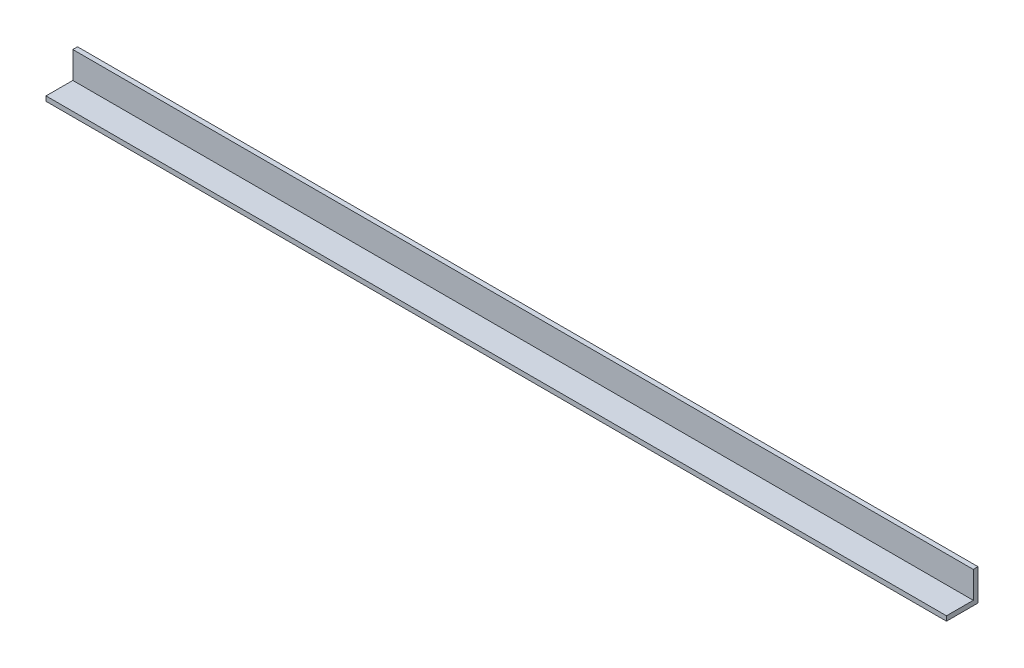
SolidWorks part; units mm, degrees
ref_plane "前视基准面" through (0, 0, 0) normal (0, 0, 1) x (1, 0, 0)
ref_plane "上视基准面" through (0, 0, 0) normal (0, 1, 0) x (1, 0, 0)
ref_plane "右视基准面" through (0, 0, 0) normal (1, 0, 0) x (0, 0, -1)
sketch "草图1" plane through (0, 0, 0) normal (0, 0, 1) x (1, 0, 0)
  line L1 (0, 0) -> (2286, 0)
  line L2 (0, 0) -> (0, 80)
  line L3 (0, 80) -> (2286, 80)
  line L4 (2286, 0) -> (2286, 80)
  dimension "D1" = 2286
  dimension "D2" = 80
extrude "拉伸1" add sketch "草图1" along normal blind 80
sketch "草图3" plane through (0, 0, 0) normal (-1, 0, 0) x (0, 0, 1)
  line L0 (80, 80) -> (80, 0) construction
  line L1 (12, 80) -> (80, 80)
  line L2 (12, 80) -> (12, 12)
  line L3 (12, 12) -> (80, 12)
  line L4 (80, 80) -> (80, 12)
  line L5 (80, 80) -> (0, 80) construction
  line L6 (80, 0) -> (0, 0) construction
  line L7 (0, 80) -> (0, 0) construction
  dimension "D1" = 12
  dimension "D2" = 12
extrude "拉伸2" cut sketch "草图3" against normal through all
